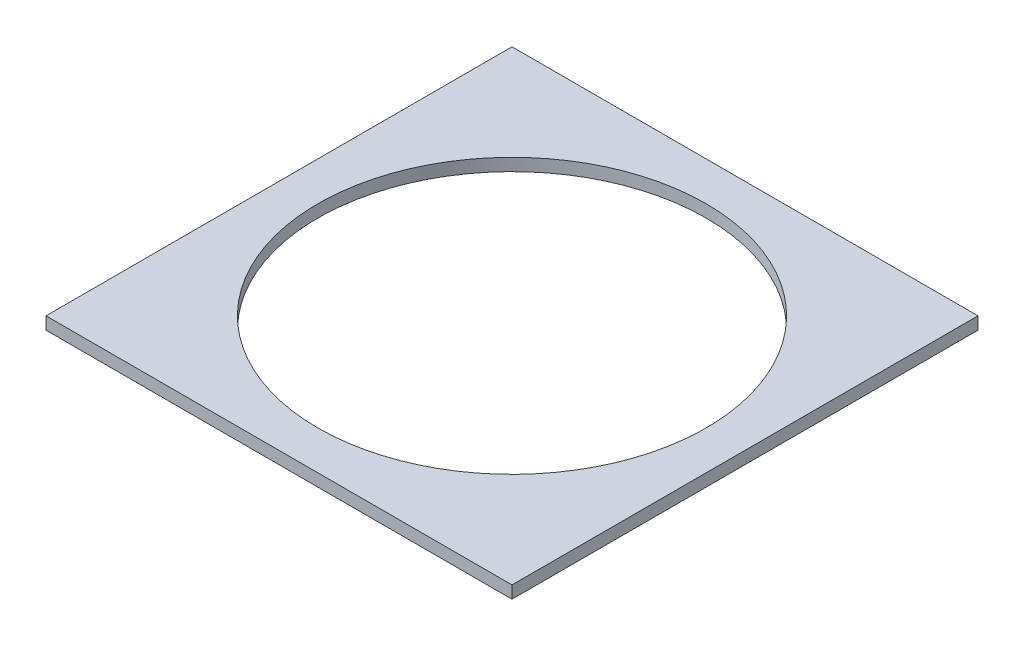
SolidWorks part; units mm, degrees
ref_plane "Front Plane" through (0, 0, 0) normal (0, 0, 1) x (1, 0, 0)
ref_plane "Top Plane" through (0, 0, 0) normal (0, 1, 0) x (1, 0, 0)
ref_plane "Right Plane" through (0, 0, 0) normal (1, 0, 0) x (0, 0, -1)
sketch "Sketch1" plane through (0, 0, 0) normal (0, 1, 0) x (1, 0, 0)
  line L1 (-150, -150) -> (150, -150)
  line L2 (-150, -150) -> (-150, 150)
  line L3 (-150, 150) -> (150, 150)
  line L4 (150, -150) -> (150, 150)
  line L5 (-150, -150) -> (150, 150) construction
  line L6 (-150, 150) -> (150, -150) construction
  point P0 (0, 0)
  dimension "D1" = 300
  dimension "D2" = 300
extrude "Boss-Extrude1" add sketch "Sketch1" along normal blind 8
sketch "Sketch2" plane through (0, 8, 0) normal (0, 1, 0) x (1, 0, 0)
  circle A0 centre (0, 0) radius 125
  dimension "D1" = 250
extrude "Cut-Extrude1" cut sketch "Sketch2" against normal blind 10
